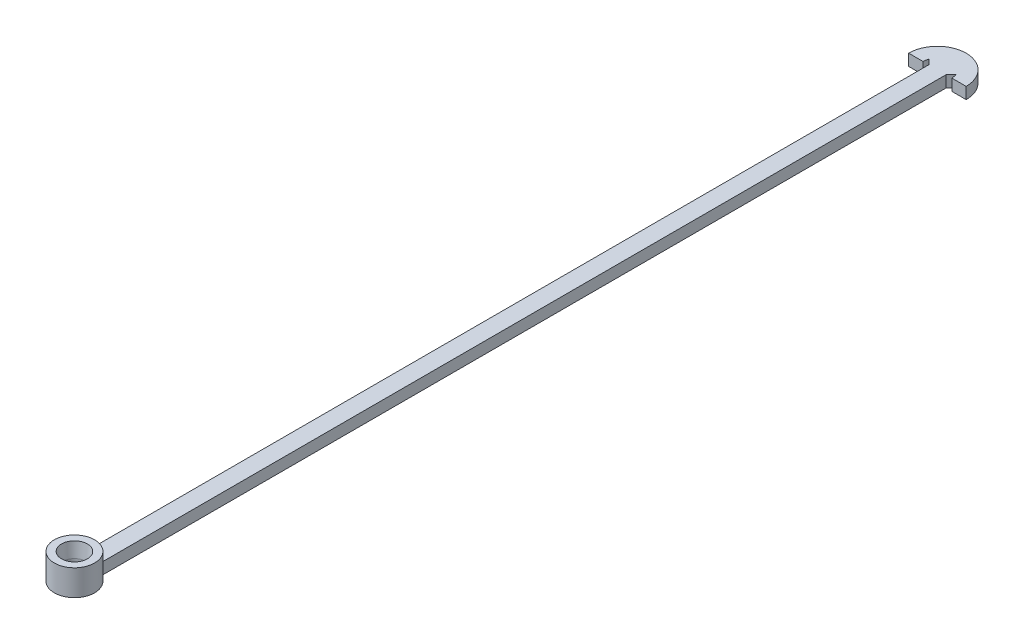
SolidWorks part; units mm, degrees
material "PET"
ref_plane "Front Plane" through (0, 0, 0) normal (0, 0, 1) x (1, 0, 0)
ref_plane "Top Plane" through (0, 0, 0) normal (0, 1, 0) x (1, 0, 0)
ref_plane "Right Plane" through (0, 0, 0) normal (1, 0, 0) x (0, 0, -1)
sketch "Sketch1" plane through (0, 0, 0) normal (0, 1, 0) x (1, 0, 0)
  line L0 (0, 0) -> (0, 300) construction
  line L1 (-3, 300) -> (-3, 6.3246)
  line L2 (3, 300) -> (3, 6.3246)
  line L3 (-5, 300) -> (-10, 300)
  line L4 (5, 300) -> (10, 300)
  line L5 (-3, 300) -> (-4.7016, 301.7016)
  line L6 (3, 300) -> (4.7016, 301.7016)
  circle A0 centre (0, 0) radius 4
  arc A1 (-3, 6.3246) -> (3, 6.3246) centre (0, 0) ccw
  arc A2 (10, 300) -> (-10, 300) centre (0, 300) ccw
  arc A3 (-4.7016, 301.7016) -> (-5, 300) centre (0, 300) ccw
  arc A4 (5, 300) -> (4.7016, 301.7016) centre (0, 300) ccw
  point P9 (-5, 300)
  point P10 (5, 300)
  dimension "D1" = 8
  dimension "D2" = 14
  dimension "D5" = 7
  dimension "D6" = 2
  dimension "D3" = 300
  dimension "D4" = 3
  dimension "D7" = 45
  dimension "D8" = 45
extrude "Boss-Extrude1" add sketch "Sketch1" along normal blind 4
ref_plane "Plane1" through (0, 9, 0) normal (0, 1, 0) x (1, 0, 0)
sketch "Sketch2" plane through (0, 9, 0) normal (0, 1, 0) x (1, 0, 0)
  circle A0 centre (0, 0) radius 7
  arc A1 (-3, 6.3246) -> (3, 6.3246) centre (0, 0) ccw construction
  circle A2 centre (0, 0) radius 4.5
  dimension "D1" = 9
sketch "Sketch3" plane through (0, 4, 0) normal (0, 1, 0) x (1, 0, 0)
  circle A0 centre (0, 0) radius 7
  arc A1 (-3, 6.3246) -> (3, 6.3246) centre (0, 0) ccw construction
  circle A2 centre (0, 0) radius 4
  circle A3 centre (0, 0) radius 4 construction
sketch "Sketch4" plane through (0, 4, 0) normal (0, 1, 0) x (1, 0, 0)
  circle A0 centre (0, 0) radius 7
  circle A1 centre (0, 0) radius 7 construction
extrude "Boss-Extrude2" add sketch "Sketch4" along normal up to surface (5 mm away) up to plane "Plane1"
loft "Cut-Loft1" cut section "Sketch2" section "Sketch3"
